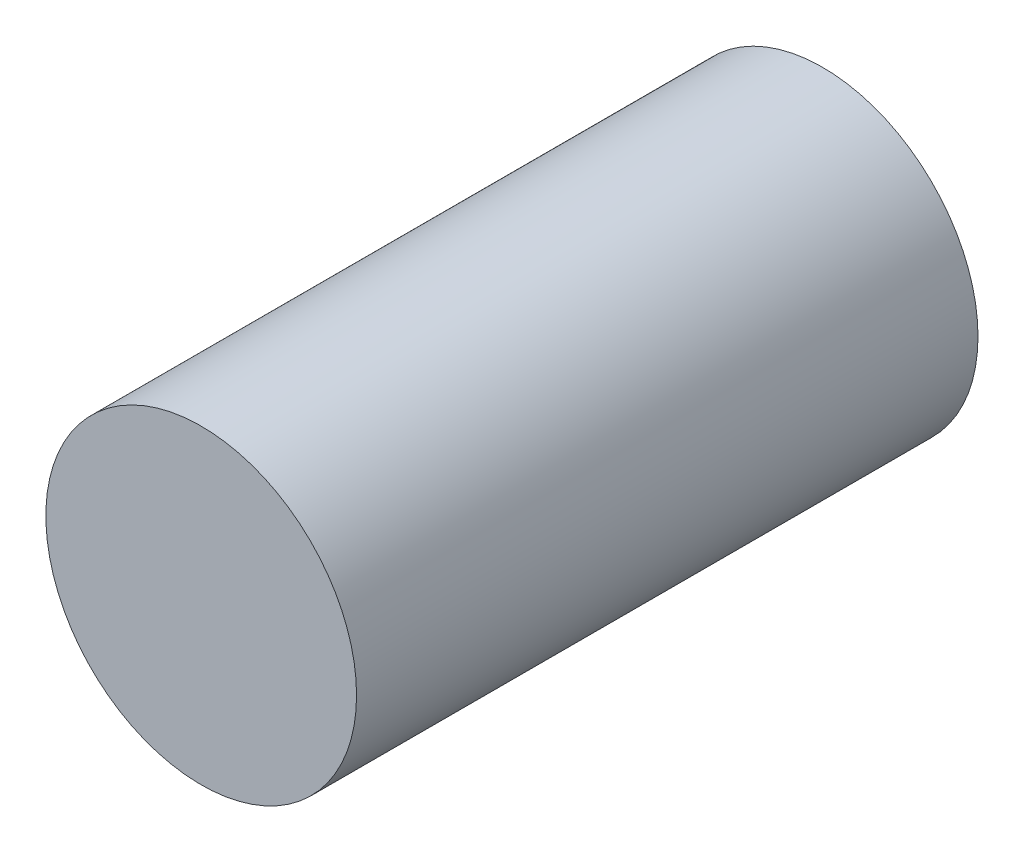
SolidWorks part; units mm, degrees
material "1.3505 (100Cr6) hardened 60 HRC"
ref_plane "Front Plane" through (0, 0, 0) normal (0, 0, 1) x (1, 0, 0)
ref_plane "Top Plane" through (0, 0, 0) normal (0, 1, 0) x (1, 0, 0)
ref_plane "Right Plane" through (0, 0, 0) normal (1, 0, 0) x (0, 0, -1)
sketch "Sketch1" plane through (0, 0, 0) normal (0, 0, 1) x (1, 0, 0)
  circle A0 centre (0, 0) radius 6
  dimension "D1" = 12
extrude "EX_Planet_Pin_Ø12x24" add sketch "Sketch1" along normal mid plane 24
